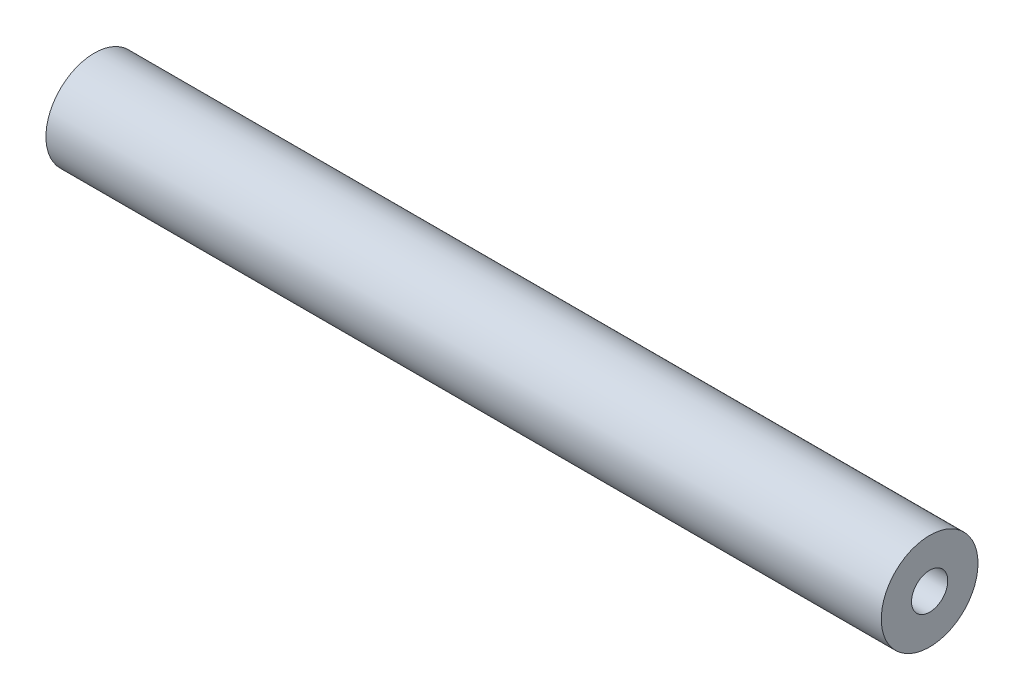
SolidWorks part; units mm, degrees
ref_plane "Front Plane" through (0, 0, 0) normal (0, 0, 1) x (1, 0, 0)
ref_plane "Top Plane" through (0, 0, 0) normal (0, 1, 0) x (1, 0, 0)
ref_plane "Right Plane" through (0, 0, 0) normal (1, 0, 0) x (0, 0, -1)
sketch "Sketch1" plane through (0, 0, 0) normal (1, 0, 0) x (0, 0, -1)
  circle A0 centre (0, 0) radius 4
  dimension "D1" = 8
extrude "Boss-Extrude1" add sketch "Sketch1" along normal blind 69.09
sketch "Sketch2" plane through (0, 0, 0) normal (-1, 0, 0) x (0, 0, 1)
  circle A0 centre (0, 0) radius 1.5
  dimension "D1" = 3
extrude "Cut-Extrude1" cut sketch "Sketch2" against normal through all
